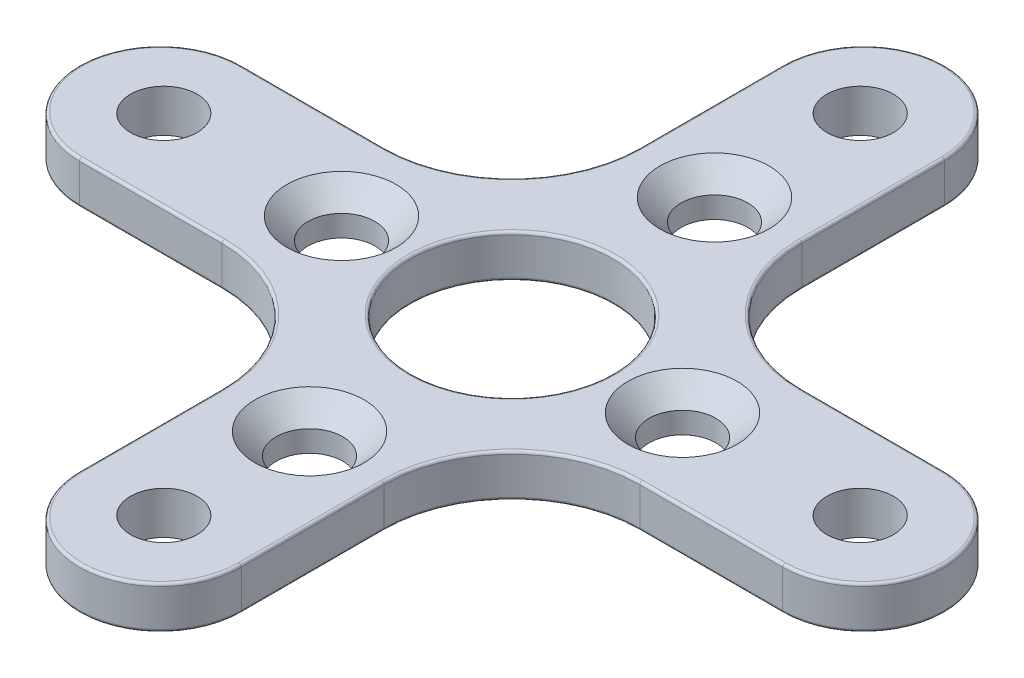
SolidWorks part; units mm, degrees
ref_plane "Front Plane" through (0, 0, 0) normal (0, 0, 1) x (1, 0, 0)
ref_plane "Top Plane" through (0, 0, 0) normal (0, 1, 0) x (1, 0, 0)
ref_plane "Right Plane" through (0, 0, 0) normal (1, 0, 0) x (0, 0, -1)
sketch "Sketch1" plane through (0, 0, 0) normal (0, 1, 0) x (1, 0, 0)
  line L0 (0, -16.5) -> (0, 16.5) construction
  line L1 (-3.8, -16.5) -> (-3.8, 16.5)
  line L2 (3.8, -16.5) -> (3.8, 16.5)
  line L3 (0, 0) -> (10.8491, 0) construction
  arc A0 (-3.8, -16.5) -> (3.8, -16.5) centre (0, -16.5) ccw
  arc A1 (3.8, 16.5) -> (-3.8, 16.5) centre (0, 16.5) ccw
  circle A2 centre (0, 16.3375) radius 1.5625
  circle A3 centre (0, -16.3375) radius 1.5625
  point P2 (0, 0)
  point P8 (0, 20.3)
  point P9 (0, -20.3)
  point P12 (0, 17.9)
  dimension "D4" = 3.125
  dimension "D1" = 7.6
  dimension "D2" = 40.6
  dimension "D3" = 2.4
extrude "Boss-Extrude1" add sketch "Sketch1" along normal blind 2
sketch3d "3DSketch1"
  line L0 (0, 0, 0) -> (0, 3, 0) construction
  dimension "D1" = 3
pattern_circular "CirPattern1" count 2 over 90 about axis through (0, 0, 0) along (0, 1, 0) of "Boss-Extrude1"
sketch "Sketch2" plane through (0, 0, 0) normal (0, 1, 0) x (1, 0, 0)
  line L0 (0, 0) -> (-1.9282, 0) construction
  line L1 (0, 0) -> (0, -2.0384) construction
  circle A0 centre (0, 9.5) radius 1.5625
  circle A1 centre (8, 0) radius 1.5625
  circle A2 centre (0, -9.5) radius 1.5625
  circle A3 centre (-8, 0) radius 1.5625
  dimension "D1" = 3.125
  dimension "D2" = 8
  dimension "D3" = 9.5
extrude "Cut-Extrude1" cut sketch "Sketch2" along normal up to surface (2 mm away) up to face at (0, 2, 0)
chamfer "Chamfer1" distance 1 angle 45 4 edges at (-8, 2, 1.5625) (0, 2, 11.0625) (8, 2, 1.5625) (0, 2, -7.9375)
fillet "Redondeo1" radius 6 4 edges at (-3.8, 1, -3.8) (-3.8, 1, 3.8) (3.8, 1, 3.8) (3.8, 1, -3.8)
sketch "Croquis1" plane through (0, 2, 0) normal (0, 1, 0) x (1, 0, 0)
  circle A0 centre (0, 0) radius 4.75
  dimension "D1" = 9.5
extrude "Cortar-Extruir1" cut sketch "Croquis1" against normal blind 10
fillet "Fillet1" radius 0.125 34 edges at (13.15, 2, 3.8) (20.3, 2, 0) (3.8, 2, 13.15) (0, 2, 20.3) (-13.15, 2, 3.8) (-20.3, 2, 0) (3.8, 2, -13.15) (0, 2, -20.3) (3.8, 0, -13.15) (0, 0, -20.3) (13.15, 0, -3.8) (20.3, 0, 0) (3.8, 0, 13.15) (0, 0, 20.3) (-13.15, 0, -3.8) (-13.15, 0, 3.8) (13.15, 2, -3.8) (-3.8, 2, 13.15) (-13.15, 2, -3.8) (-3.8, 2, -13.15) (-3.8, 0, -13.15) (13.15, 0, 3.8) (-3.8, 0, 13.15) (-20.3, 0, 0) (5.5574, 2, -5.5574) (5.5574, 2, 5.5574) (-5.5574, 2, 5.5574) (-5.5574, 2, -5.5574) (-5.5574, 0, -5.5574) (5.5574, 0, -5.5574) (5.5574, 0, 5.5574) (-5.5574, 0, 5.5574) (0, 0, 4.75) (0, 2, 4.75)
